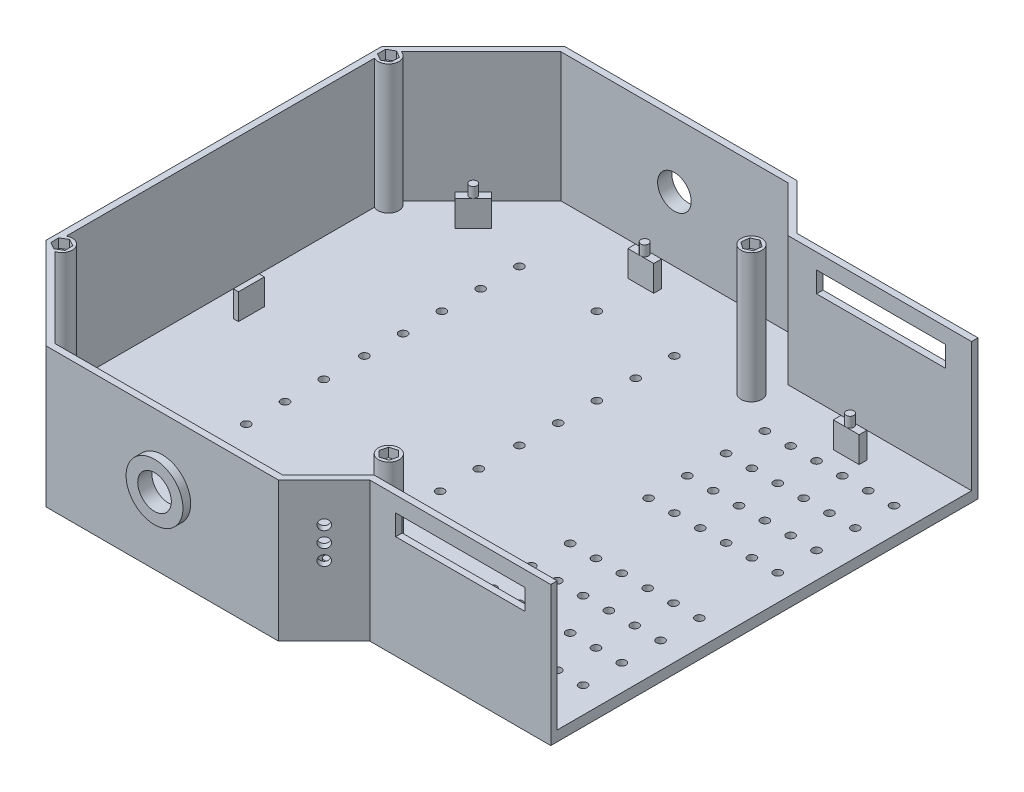
SolidWorks part; units mm, degrees
ref_plane "Ön Düzlem" through (0, 0, 0) normal (0, 0, 1) x (1, 0, 0)
ref_plane "Üst Düzlem" through (0, 0, 0) normal (0, 1, 0) x (1, 0, 0)
ref_plane "Sağ Düzlem" through (0, 0, 0) normal (1, 0, 0) x (0, 0, -1)
sketch "Çizim1" plane through (0, 0, 0) normal (0, 1, 0) x (1, 0, 0)
  line L0 (-93.9075, 105.5771) -> (-129.2628, 70.2217)
  line L1 (-129.2628, 70.2217) -> (-129.2628, -59.7783)
  line L2 (-129.2628, -59.7783) -> (-93.9075, -95.1336)
  line L3 (-93.9075, -95.1336) -> (-3.9075, -95.1336)
  line L4 (-3.9075, -95.1336) -> (13.7702, -77.4559)
  line L5 (13.7702, -77.4559) -> (83.7702, -77.4559)
  line L6 (-93.9075, 105.5771) -> (-3.9075, 105.5771)
  line L7 (-3.9075, 105.5771) -> (13.7702, 87.8994)
  line L8 (13.7702, 87.8994) -> (83.7702, 87.8994)
  line L9 (83.7702, 87.8994) -> (83.7702, -77.4559)
  dimension "D1" = 130
  dimension "D2" = 50
  dimension "D3" = 50
  dimension "D4" = 90
  dimension "D5" = 90
  dimension "D6" = 25
  dimension "D7" = 25
  dimension "D8" = 70
  dimension "D9" = 70
extrude "Yükseklik-Ekstrüzyon1" add sketch "Çizim1" along normal blind 4
ref_plane "Düzlem1" through (0, 4, 0) normal (0, 1, 0) x (1, 0, 0)
sketch "Çizim2" plane through (0, 4, 0) normal (0, 1, 0) x (1, 0, 0)
  line L0 (83.7702, 87.8994) -> (13.7702, 87.8994)
  line L2 (13.7702, 87.8994) -> (-3.9075, 105.5771)
  line L4 (-3.9075, 105.5771) -> (-93.9075, 105.5771)
  line L6 (-93.9075, 105.5771) -> (-129.2628, 70.2217)
  line L8 (-129.2628, 70.2217) -> (-129.2628, -59.7783)
  line L10 (-129.2628, -59.7783) -> (-93.9075, -95.1336)
  line L12 (-93.9075, -95.1336) -> (-3.9075, -95.1336)
  line L14 (-3.9075, -95.1336) -> (13.7702, -77.4559)
  line L16 (13.7702, -77.4559) -> (83.7702, -77.4559)
  line L18 (-126.7628, 69.1862) -> (-92.872, 103.0771)
  line L19 (-126.7628, -58.7427) -> (-126.7628, 69.1862)
  line L20 (-126.7628, -58.7427) -> (-92.872, -92.6336)
  line L21 (-92.872, -92.6336) -> (-4.943, -92.6336)
  line L22 (12.7346, -74.9559) -> (-4.943, -92.6336)
  line L23 (12.7346, -74.9559) -> (83.7702, -74.9559)
  line L24 (-4.943, 103.0771) -> (-92.872, 103.0771)
  line L25 (12.7346, 85.3994) -> (-4.943, 103.0771)
  line L26 (12.7346, 85.3994) -> (83.7702, 85.3994)
  line L27 (83.7702, -77.4559) -> (83.7702, -74.9559)
  line L28 (83.7702, 85.3994) -> (83.7702, 87.8994)
extrude "Yükseklik-Ekstrüzyon2" add sketch "Çizim2" along normal blind 50
ref_plane "Düzlem2" through (-94.5205, 0, 94.5205) normal (-0.7071, 0, 0.7071) x (0.7071, 0, 0.7071)
ref_plane "Düzlem3" through (-99.7423, 0, -99.7423) normal (-0.7071, 0, -0.7071) x (-0.7071, 0, 0.7071)
ref_plane "Düzlem4" through (-129.2628, 0, 0) normal (-1, 0, 0) x (0, 0, 1)
ref_plane "Düzlem5" through (0, 0, 95.1336) normal (0, 0, 1) x (1, 0, 0)
ref_plane "Düzlem6" through (0, 4, 0) normal (0, 1, 0) x (1, 0, 0)
ref_plane "Düzlem7" through (83.7702, 0, 0) normal (1, 0, 0) x (0, 0, -1)
ref_plane "Düzlem9" through (83.7702, 0, 0) normal (1, 0, 0) x (0, 0, -1)
ref_plane "Düzlem10" through (0, 4, 0) normal (0, 1, 0) x (1, 0, 0)
sketch "Çizim7" plane through (0, 4, 0) normal (0, 1, 0) x (1, 0, 0)
  line L2 (43.2524, 75.3994) -> (53.2524, 75.3994)
  line L4 (-6.7108, 90.7027) -> (0.3603, 83.6316)
  line L5 (-1.7611, 81.5103) -> (-8.8321, 88.5814)
  line L6 (-53.9075, 93.0771) -> (-43.9075, 93.0771)
  line L7 (-8.8321, 88.5814) -> (-6.7108, 90.7027)
  line L8 (-106.2819, 75.525) -> (-99.2108, 82.5961)
  line L9 (53.2524, 75.3994) -> (53.2524, 72.3994)
  line L10 (-116.7628, 0.2217) -> (-116.7628, 10.2217)
  line L11 (53.2524, 72.3994) -> (43.2524, 72.3994)
  line L12 (-116.7628, 10.2217) -> (-114.7628, 10.2217)
  line L13 (-114.7628, 10.2217) -> (-114.7628, 0.2217)
  line L14 (-114.7628, 0.2217) -> (-116.7628, 0.2217)
  line L15 (-99.2108, 82.5961) -> (-97.0895, 80.4748)
  line L16 (-97.0895, 80.4748) -> (-104.1606, 73.4037)
  line L17 (-104.1606, 73.4037) -> (-106.2819, 75.525)
  line L18 (-43.9075, 93.0771) -> (-43.9075, 90.0771)
  line L19 (-43.9075, 90.0771) -> (-53.9075, 90.0771)
  line L20 (-53.9075, 90.0771) -> (-53.9075, 93.0771)
  line L21 (0.3603, 83.6316) -> (-1.7611, 81.5103)
  line L24 (43.2524, 72.3994) -> (43.2524, 75.3994)
  line L26 (43.2524, -61.9559) -> (43.2524, -64.9559)
  line L27 (0.3603, -73.1882) -> (-1.7611, -71.0668)
  line L28 (-53.9075, -79.6336) -> (-53.9075, -82.6336)
  line L29 (-43.9075, -79.6336) -> (-53.9075, -79.6336)
  line L30 (-43.9075, -82.6336) -> (-43.9075, -79.6336)
  line L31 (-104.1606, -62.9602) -> (-106.2819, -65.0816)
  line L32 (-97.0895, -70.0313) -> (-104.1606, -62.9602)
  line L33 (-99.2108, -72.1526) -> (-97.0895, -70.0313)
  line L34 (53.2524, -61.9559) -> (43.2524, -61.9559)
  line L35 (53.2524, -64.9559) -> (53.2524, -61.9559)
  line L36 (-106.2819, -65.0816) -> (-99.2108, -72.1526)
  line L37 (-8.8321, -78.1379) -> (-6.7108, -80.2592)
  line L38 (-53.9075, -82.6336) -> (-43.9075, -82.6336)
  line L39 (-1.7611, -71.0668) -> (-8.8321, -78.1379)
  line L40 (-6.7108, -80.2592) -> (0.3603, -73.1882)
  line L41 (43.2524, -64.9559) -> (53.2524, -64.9559)
extrude "Yükseklik-Ekstrüzyon3" add sketch "Çizim7" along normal blind 10
ref_plane "Düzlem11" through (0, 0, 95.1336) normal (0, 0, 1) x (1, 0, 0)
sketch "Çizim8" plane through (0, 0, 95.1336) normal (0, 0, 1) x (1, 0, 0)
  line L0 (-48.9075, 0) -> (-48.9075, 29)
  line L1 (-93.9075, 0) -> (-3.9075, 0) construction
  circle A0 centre (-48.9075, 29) radius 11
  dimension "D1" = 22
  dimension "D2" = 29
extrude "Yükseklik-Ekstrüzyon5" add sketch "Çizim8" along normal blind 3
ref_plane "Düzlem13" through (0, 0, -105.5771) normal (0, 0, -1) x (-1, 0, 0)
sketch "Çizim9" plane through (0, 0, -105.5771) normal (0, 0, -1) x (-1, 0, 0)
  line L0 (48.9075, 0) -> (48.9075, 29)
  line L1 (3.9075, 0) -> (93.9075, 0) construction
  circle A0 centre (48.9075, 29) radius 11
  dimension "D1" = 22
  dimension "D2" = 29
extrude "Yükseklik-Ekstrüzyon6" add sketch "Çizim9" along normal blind 3
ref_plane "Düzlem14" through (0, 0, -108.5771) normal (0, 0, -1) x (-1, 0, 0)
sketch "Çizim11" plane through (0, 0, -108.5771) normal (0, 0, -1) x (-1, 0, 0)
  circle A0 centre (48.9075, 29) radius 6.5
  dimension "D1" = 13
extrude "Kes-Ekstrüzyon4" cut sketch "Çizim11" against normal blind 232
ref_plane "Düzlem15" through (0, 4, 0) normal (0, 1, 0) x (1, 0, 0)
sketch "Çizim12" plane through (0, 4, 0) normal (0, 1, 0) x (1, 0, 0)
  line L0 (-48.9075, 103.0771) -> (-48.9075, 73.0771)
  line L1 (-92.872, 103.0771) -> (-4.943, 103.0771) construction
  line L4 (-48.9075, -92.6336) -> (-48.9075, -62.6336)
  line L5 (-4.943, -92.6336) -> (-92.872, -92.6336) construction
  circle A0 centre (-78.9075, 73.0771) radius 1.6
  circle A1 centre (-18.9075, 73.0771) radius 1.6
  circle A2 centre (-18.9075, 58.0771) radius 1.6
  circle A3 centre (-18.9075, 43.0771) radius 1.6
  circle A4 centre (-18.9075, 28.0771) radius 1.6
  circle A5 centre (-18.9075, 13.0771) radius 1.6
  circle A6 centre (-18.9075, -2.6336) radius 1.6
  circle A7 centre (-18.9075, -17.6336) radius 1.6
  circle A8 centre (-18.9075, -32.6336) radius 1.6
  circle A9 centre (-18.9075, -47.6336) radius 1.6
  circle A10 centre (-78.9075, -47.6336) radius 1.6
  circle A11 centre (-78.9075, -62.6336) radius 1.6
  circle A12 centre (-18.9075, -62.6336) radius 1.6
  circle A13 centre (-78.9075, 58.0771) radius 1.6
  circle A14 centre (-78.9075, 43.0771) radius 1.6
  circle A15 centre (-78.9075, 28.0771) radius 1.6
  circle A16 centre (-78.9075, 13.0771) radius 1.6
  circle A17 centre (-78.9075, -2.6336) radius 1.6
  circle A18 centre (-78.9075, -17.6336) radius 1.6
  circle A19 centre (-78.9075, -32.6336) radius 1.6
  circle A20 centre (-48.9075, -62.6336) radius 1.6
  circle A21 centre (-48.9075, 73.0771) radius 1.6
  dimension "D1" = 3.2
  dimension "D2" = 3.2
  dimension "D3" = 3.2
  dimension "D4" = 3.2
  dimension "D5" = 3.2
  dimension "D6" = 3.2
  dimension "D7" = 3.2
  dimension "D8" = 3.2
  dimension "D9" = 3.2
  dimension "D10" = 3.2
  dimension "D11" = 3.2
  dimension "D12" = 3.2
  dimension "D13" = 3.2
  dimension "D14" = 3.2
  dimension "D15" = 3.2
  dimension "D16" = 3.2
  dimension "D17" = 3.2
  dimension "D18" = 3.2
  dimension "D19" = 3.2
  dimension "D20" = 3.2
  dimension "D21" = 3.2
  dimension "D22" = 3.2
extrude "Kes-Ekstrüzyon5" cut sketch "Çizim12" against normal blind 10 contours A11 | A20 | A12 | A9 | A8 | A7 | A6 | A5 | A4 | A3 | A2 | A1 | A21 | A0 | A13 | A14 | A15 | A16 | A17 | A18 | A19 | A10
sketch "Çizim13" plane through (0, 4, 0) normal (0, 1, 0) x (1, 0, 0)
  line L0 (83.7702, 85.3994) -> (83.7702, 65.3994)
  line L1 (83.7702, -74.9559) -> (83.7702, 85.3994) construction
  line L3 (83.7702, -74.9559) -> (83.7702, -54.9559)
  circle A0 centre (73.7702, 65.3994) radius 1.6
  circle A1 centre (63.7702, 65.3994) radius 1.6
  circle A2 centre (53.7702, 65.3994) radius 1.6
  circle A3 centre (43.7702, 65.3994) radius 1.6
  circle A4 centre (33.7702, 65.3994) radius 1.6
  circle A5 centre (23.7702, 65.3994) radius 1.6
  circle A6 centre (23.7702, 50.3994) radius 1.6
  circle A7 centre (33.7702, 50.3994) radius 1.6
  circle A8 centre (43.7702, 50.3994) radius 1.6
  circle A9 centre (53.7702, 50.3994) radius 1.6
  circle A10 centre (63.7702, 50.3994) radius 1.6
  circle A11 centre (73.7702, 50.3994) radius 1.6
  circle A12 centre (53.7702, 35.3994) radius 1.6
  circle A13 centre (63.7702, 35.3994) radius 1.6
  circle A14 centre (73.7702, 35.3994) radius 1.6
  circle A15 centre (73.7702, 20.3994) radius 1.6
  circle A16 centre (63.7702, 20.3994) radius 1.6
  circle A17 centre (53.7702, 20.3994) radius 1.6
  circle A18 centre (43.7702, 20.3994) radius 1.6
  circle A19 centre (43.7702, 35.3994) radius 1.6
  circle A20 centre (33.7702, 35.3994) radius 1.6
  circle A21 centre (33.7702, 20.3994) radius 1.6
  circle A22 centre (23.7702, 20.3994) radius 1.6
  circle A23 centre (23.7702, 35.3994) radius 1.6
  circle A24 centre (23.7702, -24.9559) radius 1.6
  circle A25 centre (23.7702, -9.9559) radius 1.6
  circle A26 centre (33.7702, -9.9559) radius 1.6
  circle A27 centre (33.7702, -24.9559) radius 1.6
  circle A28 centre (43.7702, -24.9559) radius 1.6
  circle A29 centre (43.7702, -9.9559) radius 1.6
  circle A30 centre (53.7702, -9.9559) radius 1.6
  circle A31 centre (63.7702, -9.9559) radius 1.6
  circle A32 centre (73.7702, -9.9559) radius 1.6
  circle A33 centre (73.7702, -24.9559) radius 1.6
  circle A34 centre (63.7702, -24.9559) radius 1.6
  circle A35 centre (53.7702, -24.9559) radius 1.6
  circle A36 centre (73.7702, -39.9559) radius 1.6
  circle A37 centre (63.7702, -39.9559) radius 1.6
  circle A38 centre (53.7702, -39.9559) radius 1.6
  circle A39 centre (43.7702, -39.9559) radius 1.6
  circle A40 centre (33.7702, -39.9559) radius 1.6
  circle A41 centre (23.7702, -39.9559) radius 1.6
  circle A42 centre (23.7702, -54.9559) radius 1.6
  circle A43 centre (33.7702, -54.9559) radius 1.6
  circle A44 centre (43.7702, -54.9559) radius 1.6
  circle A45 centre (53.7702, -54.9559) radius 1.6
  circle A46 centre (63.7702, -54.9559) radius 1.6
  circle A47 centre (73.7702, -54.9559) radius 1.6
extrude "Kes-Ekstrüzyon6" cut sketch "Çizim13" against normal blind 10 contours A42 | A43 | A44 | A45 | A46 | A47 | A36 | A37 | A38 | A39 | A40 | A41 | A24 | A27 | A28 | A35 | A34 | A33 | A32 | A31 | A30 | A29 | A26 | A25 | A22 | A21 | A18 | A17 | A16 | A15 | A14 | A11 | A0 | A1 | A10 | A13 | A12 | A9 | A2 | A3 | A8 | A19 | A20 | A23 | A6 | A7 | A4 | A5
ref_plane "Düzlem16" through (-129.2628, 0, 0) normal (-1, 0, 0) x (0, 0, 1)
ref_plane "Düzlem17" through (0, 0, 77.4559) normal (0, 0, 1) x (1, 0, 0)
sketch "Çizim15" plane through (0, 0, 77.4559) normal (0, 0, 1) x (1, 0, 0)
  line L8 (73.7702, 48) -> (23.7702, 48)
  line L9 (23.7702, 48) -> (23.7702, 40)
  line L10 (23.7702, 40) -> (73.7702, 40)
  line L11 (73.7702, 40) -> (73.7702, 48)
extrude "Kes-Ekstrüzyon8" cut sketch "Çizim15" against normal blind 190
ref_plane "Düzlem18" through (0, 4, 0) normal (0, 1, 0) x (1, 0, 0)
sketch "Çizim16" plane through (0, 4, 0) normal (0, 1, 0) x (1, 0, 0)
  circle A2 centre (8.5925, 75.3994) radius 4
  circle A3 centre (-124.9151, 68.4208) radius 4
  circle A4 centre (-124.9151, -57.9774) radius 4
  circle A5 centre (8.5925, -64.9559) radius 4
  dimension "D1" = 8
  dimension "D2" = 8
  dimension "D3" = 8
  dimension "D4" = 8
extrude "Yükseklik-Ekstrüzyon7" add sketch "Çizim16" along normal up to surface (50 mm away) up to face at (-25.7611, 54, -5.2217)
ref_plane "Düzlem19" through (0, 54, 0) normal (0, 1, 0) x (1, 0, 0)
sketch "Çizim17" plane through (0, 54, 0) normal (0, 1, 0) x (1, 0, 0)
  circle A0 centre (-124.9151, 68.4208) radius 1.6
  circle A1 centre (-124.9151, -57.9774) radius 1.6
  circle A2 centre (8.5925, 75.3994) radius 1.6
  circle A3 centre (8.5925, -64.9559) radius 1.6
  dimension "D1" = 3.2
  dimension "D2" = 3.2
  dimension "D3" = 3.2
  dimension "D4" = 3.2
extrude "Kes-Ekstrüzyon9" cut sketch "Çizim17" against normal blind 190
sketch "Çizim18" plane through (0, 54, 0) normal (0, 1, 0) x (1, 0, 0)
  line L1 (-122.2397, 66.8548) -> (-122.2212, 69.9548)
  line L2 (-122.2212, 69.9548) -> (-124.8965, 71.5208)
  line L3 (-124.8965, 71.5208) -> (-127.5904, 69.9869)
  line L4 (-127.5904, 69.9869) -> (-127.609, 66.8869)
  line L5 (-127.609, 66.8869) -> (-124.9336, 65.3209)
  line L6 (-124.9336, 65.3209) -> (-122.2397, 66.8548)
  line L7 (-122.1984, -59.4705) -> (-122.2636, -56.3712)
  line L8 (-122.2636, -56.3712) -> (-124.9803, -54.878)
  line L9 (-124.9803, -54.878) -> (-127.6318, -56.4842)
  line L10 (-127.6318, -56.4842) -> (-127.5665, -59.5835)
  line L11 (-127.5665, -59.5835) -> (-124.8498, -61.0767)
  line L12 (-124.8498, -61.0767) -> (-122.1984, -59.4705)
  line L13 (10.8202, -67.1117) -> (11.5733, -64.1046)
  line L14 (11.5733, -64.1046) -> (9.3456, -61.9488)
  line L15 (9.3456, -61.9488) -> (6.3648, -62.8001)
  line L16 (6.3648, -62.8001) -> (5.6117, -65.8073)
  line L17 (5.6117, -65.8073) -> (7.8394, -67.9631)
  line L18 (7.8394, -67.9631) -> (10.8202, -67.1117)
  line L19 (11.1104, 73.591) -> (11.4176, 76.6757)
  line L20 (11.4176, 76.6757) -> (8.8997, 78.4842)
  line L21 (8.8997, 78.4842) -> (6.0746, 77.2078)
  line L22 (6.0746, 77.2078) -> (5.7674, 74.1231)
  line L23 (5.7674, 74.1231) -> (8.2853, 72.3147)
  line L24 (8.2853, 72.3147) -> (11.1104, 73.591)
  circle A0 centre (-124.9151, 68.4208) radius 2.6847 construction
  circle A1 centre (-124.9151, -57.9774) radius 2.6847 construction
  circle A2 centre (8.5925, -64.9559) radius 2.6847 construction
  circle A3 centre (8.5925, 75.3994) radius 2.6847 construction
  dimension "D1" = 6.2
  dimension "D2" = 6.2
  dimension "D3" = 6.2
  dimension "D4" = 6.2
extrude "Kes-Ekstrüzyon10" cut sketch "Çizim18" against normal blind 3.5
sketch "Çizim19" plane through (0, 4, 0) normal (0, 1, 0) x (1, 0, 0)
  circle A0 centre (-101.6857, 77.9999) radius 1.5
  circle A2 centre (-101.6857, -67.5564) radius 1.5
  circle A3 centre (-48.9075, -81.1336) radius 1.5
  circle A4 centre (-4.2359, -75.663) radius 1.5
  circle A5 centre (48.2524, -63.4559) radius 1.5
  circle A6 centre (-48.9075, 91.5771) radius 1.5
  circle A7 centre (-4.2359, 86.1065) radius 1.5
  circle A8 centre (48.2524, 73.8994) radius 1.5
  dimension "D1" = 3
extrude "Yükseklik-Ekstrüzyon8" add sketch "Çizim19" along normal blind 14
ref_plane "Düzlem20" through (45.613, 0, 45.613) normal (0.7071, 0, 0.7071) x (0.7071, 0, -0.7071)
sketch "Çizim20" plane through (45.613, 0, 45.613) normal (0.7071, 0, 0.7071) x (0.7071, 0, -0.7071)
  circle A0 centre (-57.5326, 39) radius 2
  circle A1 centre (-57.5326, 33) radius 2
  circle A2 centre (-57.5326, 27) radius 2
  dimension "D5" = 4
  dimension "D6" = 4
  dimension "D7" = 4
  dimension "D2" = 6
  dimension "D3" = 6
extrude "Kes-Ekstrüzyon11" cut sketch "Çizim20" against normal blind 14
ref_plane "Düzlem21" through (50.8348, 0, -50.8348) normal (0.7071, 0, -0.7071) x (-0.7071, 0, -0.7071)
sketch "Çizim21" plane through (50.8348, 0, -50.8348) normal (0.7071, 0, -0.7071) x (-0.7071, 0, -0.7071)
  circle A0 centre (64.9173, 39) radius 2
  circle A1 centre (64.9173, 33) radius 2
  circle A2 centre (64.9173, 27) radius 2
  dimension "D4" = 4
  dimension "D5" = 4
  dimension "D6" = 4
  dimension "D2" = 6
  dimension "D3" = 6
extrude "Kes-Ekstrüzyon12" cut sketch "Çizim21" against normal blind 14
